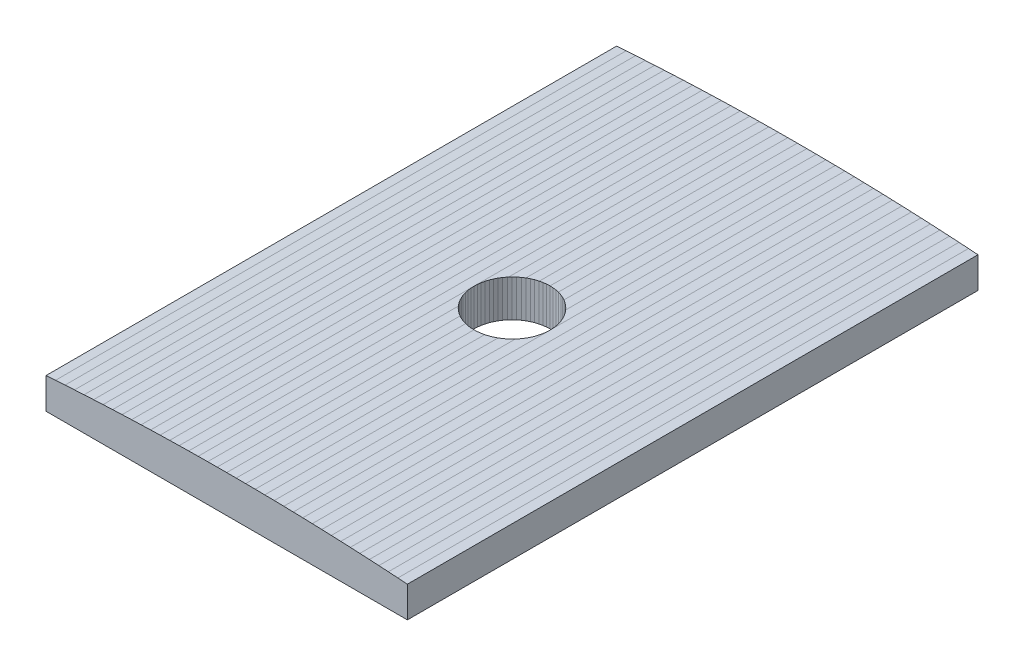
SolidWorks part; units mm, degrees
ref_plane "前视基准面" through (0, 0, 0) normal (0, 0, 1) x (1, 0, 0)
ref_plane "上视基准面" through (0, 0, 0) normal (0, 1, 0) x (1, 0, 0)
ref_plane "右视基准面" through (0, 0, 0) normal (1, 0, 0) x (0, 0, -1)
other "Configuration Table"
sketch "草图1" plane through (0, 0, 0) normal (0, 0, 1) x (1, 0, 0)
  line L0 (-190, 96) -> (190, 96)
  line L1 (190, 96) -> (190, 128.534)
  line L2 (190, 128.534) -> (180, 129.2145)
  line L3 (180, 129.2145) -> (170, 129.8583)
  line L4 (170, 129.8583) -> (160, 130.4652)
  line L5 (160, 130.4652) -> (150, 131.0354)
  line L6 (150, 131.0354) -> (140, 131.5687)
  line L7 (140, 131.5687) -> (130, 132.0653)
  line L8 (130, 132.0653) -> (120, 132.5251)
  line L9 (120, 132.5251) -> (110, 132.9481)
  line L10 (110, 132.9481) -> (100, 133.3344)
  line L11 (100, 133.3344) -> (90, 133.6838)
  line L12 (90, 133.6838) -> (80, 133.9965)
  line L13 (80, 133.9965) -> (70, 134.2724)
  line L14 (70, 134.2724) -> (60, 134.5115)
  line L15 (60, 134.5115) -> (50, 134.7138)
  line L16 (50, 134.7138) -> (40, 134.8793)
  line L17 (40, 134.8793) -> (30, 135.0081)
  line L18 (30, 135.0081) -> (20, 135.1)
  line L19 (20, 135.1) -> (10, 135.1552)
  line L20 (10, 135.1552) -> (0, 135.1736)
  line L21 (0, 135.1736) -> (-10, 135.1552)
  line L22 (-10, 135.1552) -> (-20, 135.1)
  line L23 (-20, 135.1) -> (-30, 135.0081)
  line L24 (-30, 135.0081) -> (-40, 134.8793)
  line L25 (-40, 134.8793) -> (-50, 134.7138)
  line L26 (-50, 134.7138) -> (-60, 134.5115)
  line L27 (-60, 134.5115) -> (-70, 134.2724)
  line L28 (-70, 134.2724) -> (-80, 133.9965)
  line L29 (-80, 133.9965) -> (-90, 133.6838)
  line L30 (-90, 133.6838) -> (-100, 133.3344)
  line L31 (-100, 133.3344) -> (-110, 132.9481)
  line L32 (-110, 132.9481) -> (-120, 132.5251)
  line L33 (-120, 132.5251) -> (-130, 132.0653)
  line L34 (-130, 132.0653) -> (-140, 131.5687)
  line L35 (-140, 131.5687) -> (-150, 131.0354)
  line L36 (-150, 131.0354) -> (-160, 130.4652)
  line L37 (-160, 130.4652) -> (-170, 129.8583)
  line L38 (-170, 129.8583) -> (-180, 129.2145)
  line L39 (-180, 129.2145) -> (-190, 128.534)
  line L40 (-190, 128.534) -> (-190, 96)
  dimension "x0" = 190
  dimension "x1" = 190
  dimension "x3" = 180
  dimension "x4" = 170
  dimension "x5" = 160
  dimension "x6" = 150
  dimension "x7" = 140
  dimension "x8" = 130
  dimension "x9" = 120
  dimension "x10" = 110
  dimension "x11" = 100
  dimension "x12" = 90
  dimension "x13" = 80
  dimension "x14" = 70
  dimension "x15" = 60
  dimension "x16" = 50
  dimension "x17" = 40
  dimension "x18" = 30
  dimension "x19" = 20
  dimension "x20" = 10
  dimension "x22" = 10
  dimension "x23" = 20
  dimension "x24" = 30
  dimension "x25" = 40
  dimension "x26" = 50
  dimension "x27" = 60
  dimension "x28" = 70
  dimension "x29" = 80
  dimension "x30" = 90
  dimension "x31" = 100
  dimension "x32" = 110
  dimension "x33" = 120
  dimension "x34" = 130
  dimension "x35" = 140
  dimension "x36" = 150
  dimension "x37" = 160
  dimension "x38" = 170
  dimension "x39" = 180
  dimension "y0" = 96
  dimension "y2" = 128.534
  dimension "y3" = 129.2145
  dimension "y4" = 129.8583
  dimension "y5" = 130.4652
  dimension "y6" = 131.0354
  dimension "y7" = 131.5687
  dimension "y8" = 132.0653
  dimension "y9" = 132.5251
  dimension "y10" = 132.9481
  dimension "y11" = 133.3344
  dimension "y12" = 133.6838
  dimension "y13" = 133.9965
  dimension "y14" = 134.2724
  dimension "y15" = 134.5115
  dimension "y16" = 134.7138
  dimension "y17" = 134.8793
  dimension "y18" = 135.0081
  dimension "y19" = 135.1
  dimension "y20" = 135.1552
  dimension "y21" = 135.1736
  dimension "y22" = 135.1552
  dimension "y23" = 135.1
  dimension "y24" = 135.0081
  dimension "y25" = 134.8793
  dimension "y26" = 134.7138
  dimension "y27" = 134.5115
  dimension "y28" = 134.2724
  dimension "y29" = 133.9965
  dimension "y30" = 133.6838
  dimension "y31" = 133.3344
  dimension "y32" = 132.9481
  dimension "y33" = 132.5251
  dimension "y34" = 132.0653
  dimension "y35" = 131.5687
  dimension "y36" = 131.0354
  dimension "y37" = 130.4652
  dimension "y38" = 129.8583
  dimension "y39" = 129.2145
  dimension "y40" = 128.534
extrude "Arched_float" add sketch "草图1" along normal blind 600
sketch "草图2" plane through (0, 0, 0) normal (0, 1, 0) x (1, 0, 0)
  line L0 (40, -300) -> (39.8478, -303.4862)
  line L1 (39.8478, -303.4862) -> (39.3923, -306.9459)
  line L2 (39.3923, -306.9459) -> (38.637, -310.3528)
  line L3 (38.637, -310.3528) -> (37.5877, -313.6808)
  line L4 (37.5877, -313.6808) -> (36.2523, -316.9047)
  line L5 (36.2523, -316.9047) -> (34.641, -320)
  line L6 (34.641, -320) -> (32.7661, -322.9431)
  line L7 (32.7661, -322.9431) -> (30.6418, -325.7115)
  line L8 (30.6418, -325.7115) -> (28.2843, -328.2843)
  line L9 (28.2843, -328.2843) -> (25.7115, -330.6418)
  line L10 (25.7115, -330.6418) -> (22.9431, -332.7661)
  line L11 (22.9431, -332.7661) -> (20, -334.641)
  line L12 (20, -334.641) -> (16.9047, -336.2523)
  line L13 (16.9047, -336.2523) -> (13.6808, -337.5877)
  line L14 (13.6808, -337.5877) -> (10.3528, -338.637)
  line L15 (10.3528, -338.637) -> (6.9459, -339.3923)
  line L16 (6.9459, -339.3923) -> (3.4862, -339.8478)
  line L17 (3.4862, -339.8478) -> (0, -340)
  line L18 (0, -340) -> (-3.4862, -339.8478)
  line L19 (-3.4862, -339.8478) -> (-6.9459, -339.3923)
  line L20 (-6.9459, -339.3923) -> (-10.3528, -338.637)
  line L21 (-10.3528, -338.637) -> (-13.6808, -337.5877)
  line L22 (-13.6808, -337.5877) -> (-16.9047, -336.2523)
  line L23 (-16.9047, -336.2523) -> (-20, -334.641)
  line L24 (-20, -334.641) -> (-22.9431, -332.7661)
  line L25 (-22.9431, -332.7661) -> (-25.7115, -330.6418)
  line L26 (-25.7115, -330.6418) -> (-28.2843, -328.2843)
  line L27 (-28.2843, -328.2843) -> (-30.6418, -325.7115)
  line L28 (-30.6418, -325.7115) -> (-32.7661, -322.9431)
  line L29 (-32.7661, -322.9431) -> (-34.641, -320)
  line L30 (-34.641, -320) -> (-36.2523, -316.9047)
  line L31 (-36.2523, -316.9047) -> (-37.5877, -313.6808)
  line L32 (-37.5877, -313.6808) -> (-38.637, -310.3528)
  line L33 (-38.637, -310.3528) -> (-39.3923, -306.9459)
  line L34 (-39.3923, -306.9459) -> (-39.8478, -303.4862)
  line L35 (-39.8478, -303.4862) -> (-40, -300)
  line L36 (-40, -300) -> (-39.8478, -296.5138)
  line L37 (-39.8478, -296.5138) -> (-39.3923, -293.0541)
  line L38 (-39.3923, -293.0541) -> (-38.637, -289.6472)
  line L39 (-38.637, -289.6472) -> (-37.5877, -286.3192)
  line L40 (-37.5877, -286.3192) -> (-36.2523, -283.0953)
  line L41 (-36.2523, -283.0953) -> (-34.641, -280)
  line L42 (-34.641, -280) -> (-32.7661, -277.0569)
  line L43 (-32.7661, -277.0569) -> (-30.6418, -274.2885)
  line L44 (-30.6418, -274.2885) -> (-28.2843, -271.7157)
  line L45 (-28.2843, -271.7157) -> (-25.7115, -269.3582)
  line L46 (-25.7115, -269.3582) -> (-22.9431, -267.2339)
  line L47 (-22.9431, -267.2339) -> (-20, -265.359)
  line L48 (-20, -265.359) -> (-16.9047, -263.7477)
  line L49 (-16.9047, -263.7477) -> (-13.6808, -262.4123)
  line L50 (-13.6808, -262.4123) -> (-10.3528, -261.363)
  line L51 (-10.3528, -261.363) -> (-6.9459, -260.6077)
  line L52 (-6.9459, -260.6077) -> (-3.4862, -260.1522)
  line L53 (-3.4862, -260.1522) -> (0, -260)
  line L54 (0, -260) -> (3.4862, -260.1522)
  line L55 (3.4862, -260.1522) -> (6.9459, -260.6077)
  line L56 (6.9459, -260.6077) -> (10.3528, -261.363)
  line L57 (10.3528, -261.363) -> (13.6808, -262.4123)
  line L58 (13.6808, -262.4123) -> (16.9047, -263.7477)
  line L59 (16.9047, -263.7477) -> (20, -265.359)
  line L60 (20, -265.359) -> (22.9431, -267.2339)
  line L61 (22.9431, -267.2339) -> (25.7115, -269.3582)
  line L62 (25.7115, -269.3582) -> (28.2843, -271.7157)
  line L63 (28.2843, -271.7157) -> (30.6418, -274.2885)
  line L64 (30.6418, -274.2885) -> (32.7661, -277.0569)
  line L65 (32.7661, -277.0569) -> (34.641, -280)
  line L66 (34.641, -280) -> (36.2523, -283.0953)
  line L67 (36.2523, -283.0953) -> (37.5877, -286.3192)
  line L68 (37.5877, -286.3192) -> (38.637, -289.6472)
  line L69 (38.637, -289.6472) -> (39.3923, -293.0541)
  line L70 (39.3923, -293.0541) -> (39.8478, -296.5138)
  line L71 (39.8478, -296.5138) -> (40, -300)
extrude "Tether_pass_through" cut sketch "草图2" against normal through all and the other way through all
